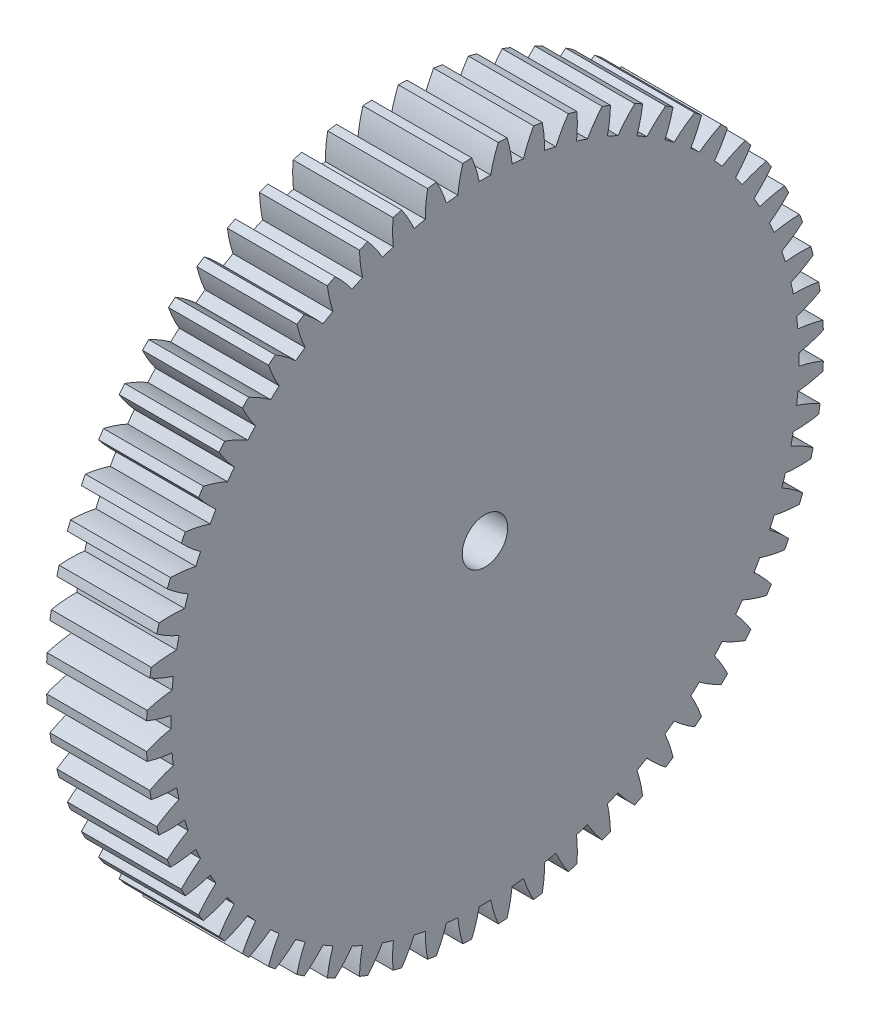
SolidWorks part; units mm, degrees
ref_plane "Plane1" through (0, 0, 0) normal (0, 0, 1) x (1, 0, 0)
ref_plane "Plane2" through (0, 0, 0) normal (0, 1, 0) x (1, 0, 0)
ref_plane "Plane3" through (0, 0, 0) normal (1, 0, 0) x (0, 0, -1)
other "Configuration Table"
sketch "HoldingSke" plane through (0, 0, 0) normal (0, 1, 0) x (1, 0, 0)
  line L0 (0, 0) -> (0.8333, -1.4434)
  line L1 (-15, 0) -> (100, 0) construction
  line L2 (0, 0) -> (-2.1039, 2.3779)
  line L3 (0, 0) -> (-11.863, 4.5341)
  line L4 (0, 0) -> (4.318, 7.479)
  line L5 (0, 0) -> (-46.8476, -17.4728)
  line L6 (0, 0) -> (-4.551, -3.0706)
  line L7 (-2.1039, 2.3779) -> (8.6586, 51.2059)
  line L8 (-76.2, 54.61) -> (-76.1, 54.61)
  line L9 (-67.7845, 28.3722) -> (-49.3413, 33.142)
  line L10 (-76.2, 71.12) -> (104.1128, 71.12)
  line L11 (0, 0) -> (-5.49, 0)
  line L12 (-76.2, 101.6) -> (-76.177, 101.6)
  line L13 (24.9733, 27.94) -> (52.9518, 28.4284)
  line L14 (24.9733, 27.94) -> (24.9743, 27.94)
  line L15 (24.9733, 27.94) -> (100.4006, 29.5858)
  line L16 (-63.627, -0.6) -> (-12.827, -0.6)
  circle A0 centre (0, 0) radius 0.4
  circle A1 centre (0, 0) radius 17.249
  circle A2 centre (0, 0) radius 37.5
  circle A3 centre (0, 0) radius 0.4
  dimension "MHD" = 34.498
  dimension "Hub_dia" = 75
  dimension "Bore" = 0.8
  dimension "MBD" = 0.8
  dimension "Num_teeth" = 60
  dimension "Pitch" = 1.6667
  dimension "Overall_len" = 50
  dimension "Show_teeth" = 60
  dimension "Thickness" = 5.49
  dimension "OAL" = 50.0001
  dimension "T_dim" = 0.1
  dimension "Ap" = 14.5
  dimension "H" = 19.05
  dimension "Pitch_radius" = 180.3128
  dimension "Width" = 5.49
  dimension "Backlash" = 0.023
  dimension "Addendum_fac" = 1
  dimension "Dedendum_fac" = 1.25
  dimension "Clearance_fac" = 0.25
  dimension "Dedendum_add" = 0.001
  dimension "Module" = 0.6
sketch "BasProSke" plane through (0, 0, 0) normal (0, 1, 0) x (1, 0, 0)
  line L0 (-10, 0) -> (60, 0) construction
  line L1 (0, 0) -> (0, 18.6)
  line L2 (0, 0) -> (5.49, 0)
  line L3 (5.49, 0) -> (5.49, 18.6)
  line L4 (5.49, 18.6) -> (0, 18.6)
  dimension "Thickness" = 5.49
  dimension "Diameter" = 37.2
revolve "Base-Revolve" add sketch "BasProSke" angle 360 about L0
sketch "TooCutSke" plane through (0, 0, 0) normal (1, 0, 0) x (0, 0, -1)
  line L1 (0, 0) -> (0, 107) construction
  line L2 (0, 0) -> (-0.5114, 17.9927) construction
  line L3 (0, 0) -> (-1.8836, 35.9404) construction
  line L4 (-0.5114, 17.9927) -> (-0.9418, 17.9702) construction
  arc A0 (0.3153, 17.2461) -> (-0.3153, 17.2461) centre (0, 0) ccw
  arc A1 (0.7414, 18.6106) -> (-0.7414, 18.6106) centre (0, 0) ccw
  circle A2 centre (0, 0) radius 18 construction
  circle A3 centre (0, 0) radius 17.4267 construction
  arc A4 (-0.3153, 17.2461) -> (-0.7414, 18.6106) centre (-7.3671, 15.7928) ccw
  arc A5 (0.7414, 18.6106) -> (0.3153, 17.2461) centre (7.3671, 15.7928) ccw
  dimension "Root_dia" = 34.498
  dimension "Overcut_dia" = 37.2508
  dimension "Pitch_dia" = 36
  dimension "Base_dia" = 34.8533
  dimension "Flank_rad" = 7.2
  dimension "Half_ang" = 3
  dimension "Half_CT" = 0.4309
extrude "ToothCut" cut sketch "TooCutSke" along normal through all
fillet "Breaks" [suppressed] radius 0.012
fillet "RootFillets" [suppressed] radius 0.151
pattern_circular "TeethCuts" count 60 every 6 about axis through (-10, 0, 0) along (1, 0, 0) of "ToothCut", "RootFillets", "Breaks"
sketch "HubNeaOneSke" plane through (0, 0, 0) normal (-1, 0, 0) x (0, 0, 1)
  circle A0 centre (0, 0) radius 17.249
  dimension "Diameter" = 34.498
extrude "HubNearOne" [suppressed] add sketch "HubNeaOneSke" along normal blind 44.5101
sketch "HubNeaBotSke" plane through (0, 0, 0) normal (-1, 0, 0) x (0, 0, 1)
  circle A0 centre (0, 0) radius 17.249
  dimension "Diameter" = 34.498
extrude "HubNearBoth" [suppressed] add sketch "HubNeaBotSke" along normal blind 22.255
ref_plane "FarPln" through (5.49, 0, 0) normal (1, 0, 0) x (0, 0, -1)
sketch "HubFarSke" plane through (5.49, 0, 0) normal (1, 0, 0) x (0, 0, -1)
  circle A0 centre (0, 0) radius 17.249
  dimension "Diameter" = 34.498
extrude "HubFar" [suppressed] add sketch "HubFarSke" along normal blind 22.255
sketch "BorSke" plane through (0, 0, 0) normal (1, 0, 0) x (0, 0, -1)
  circle A0 centre (0, 0) radius 0.4
  dimension "Diameter" = 0.8
extrude "Bore" cut sketch "BorSke" along normal mid plane 100.0001
sketch "KeySke" plane through (0, 0, 0) normal (1, 0, 0) x (0, 0, -1)
  line L0 (-0.05, 0) -> (-0.05, 0.5)
  line L1 (-0.05, 0.5) -> (0.05, 0.5)
  line L2 (0.05, 0.5) -> (0.05, 0)
  line L3 (0, 0) -> (0, 34) construction
  line L4 (-0.05, 0) -> (0.05, 0)
  dimension "Offset" = 0.5
  dimension "Width" = 0.1
extrude "Keyway" [suppressed] cut sketch "KeySke" along normal mid plane 100.0001
pattern_circular "Keyway2" [suppressed] count 2 every 90 about axis through (-10, 0, 0) along (1, 0, 0)
sketch "Sketch1" plane through (5.49, 0, 0) normal (1, 0, 0) x (0, 0, -1)
  circle A0 centre (0, 0) radius 1.25
  dimension "D1" = 2.5
extrude "Cut-Extrude1" cut sketch "Sketch1" against normal through all
equation "' \"Module@HoldingSke\" = 6.35"
equation "' \"Num_teeth@HoldingSke\" = 12"
equation "' \"Ap@HoldingSke\" =  20"
equation "' \"Ap@HoldingSke\" = 20"
equation "' \"Width@HoldingSke\" = 0.5 * 25.4"
equation "' \"Hub_dia@HoldingSke\"= 1 * 25.4"
equation "' \"Hub_dia@HoldingSke\" = 1 * 25.4"
equation "' \"Overall_len@HoldingSke\" = 1.0 * 25.4"
equation "' \"Bore@HoldingSke\" = 0.75 * 25.4"
equation "' \"T_dim@HoldingSke\" = 0.1 * 25.4"
equation "' \"Width@KeySke\" = 0.25 * 25.4"
equation "' \"Show_teeth@HoldingSke\" = 13"
equation "' \"Backlash@HoldingSke\" = 0.009 * 25.4"
equation "' \"Addendum_fac@HoldingSke\" = 1.0"
equation "' \"Dedendum_fac@HoldingSke\" = 1.25"
equation "' \"Dedendum_add@HoldingSke\" = 0.00005 * 25.4"
equation "' \"Clearance_fac@HoldingSke\" = 0.25"
equation "\"Pitch@HoldingSke\" = 1 / \"Module@HoldingSke\""
equation "\"Overcut_dia@TooCutSke\" = (\"Num_teeth@HoldingSke\" + 2 * \"Addendum_fac@HoldingSke\") / \"Pitch@HoldingSke\" + 0.002 * 25.4"
equation "\"Pitch_dia@TooCutSke\" = \"Num_teeth@HoldingSke\" / \"Pitch@HoldingSke\""
equation "\"Base_dia@TooCutSke\" = \"Num_teeth@HoldingSke\" / \"Pitch@HoldingSke\" * cos((\"Ap@HoldingSke\"  * 3.14159265 / 180))"
equation "\"Root_dia@TooCutSke\" = (\"Num_teeth@HoldingSke\" + 2) / \"Pitch@HoldingSke\" - 2 * (\"Addendum_fac@HoldingSke\" + \"Dedendum_fac@HoldingSke\") / \"Pitch@HoldingSke\" - \"Dedendum_add@HoldingSke\" * 2"
equation "\"Half_ang@TooCutSke\" = 180 / \"Num_teeth@HoldingSke\""
equation "\"Half_CT@TooCutSke\" = \"Num_teeth@HoldingSke\" / \"Pitch@HoldingSke\" * sin((3.14159265 / 2 / \"Num_teeth@HoldingSke\")) / 2 - 7 * \"Backlash@HoldingSke\" / 4"
equation "\"Flank_rad@TooCutSke\" = \"Num_teeth@HoldingSke\" / \"Pitch@HoldingSke\" / 5"
equation "\"Radius@RootFillets\" = \"Clearance_fac@HoldingSke\" / \"Pitch@HoldingSke\" + \"Dedendum_add@HoldingSke\""
equation "\"Break_rad@Breaks\" = 0.02 / \"Pitch@HoldingSke\""
equation "\"Thickness@HoldingSke\" = \"Width@HoldingSke\""
equation "\"OAL@HoldingSke\" = \"Thickness@HoldingSke\""
equation "\"MHD@HoldingSke\" = (\"Num_teeth@HoldingSke\" + 2) / \"Pitch@HoldingSke\" - 2 * (\"Addendum_fac@HoldingSke\" + \"Dedendum_fac@HoldingSke\")  / \"Pitch@HoldingSke\" - \"Dedendum_add@HoldingSke\" * 2"
equation "\"MBD@HoldingSke\" = (\"Num_teeth@HoldingSke\" + 2) / \"Pitch@HoldingSke\" - 2 * (\"Addendum_fac@HoldingSke\" + \"Dedendum_fac@HoldingSke\")  / \"Pitch@HoldingSke\" - \"Dedendum_add@HoldingSke\" * 2 - 0.002 * 25.4"
equation "\"MHD@HoldingSke\" = ((sgn( \"MHD@HoldingSke\" - \"Hub_dia@HoldingSke\" )-1)*( \"MHD@HoldingSke\" - \"Hub_dia@HoldingSke\" ))/-2+ \"Hub_dia@HoldingSke\""
equation "\"MBD@HoldingSke\" = ((sgn( \"MBD@HoldingSke\" - \"Bore@HoldingSke\" )-1)*( \"MBD@HoldingSke\" - \"Bore@HoldingSke\" ))/-2+ \"Bore@HoldingSke\""
equation "\"OAL@HoldingSke\" = ((sgn( \"OAL@HoldingSke\" - \"Overall_len@HoldingSke\" )+1)*( \"OAL@HoldingSke\" - \"Overall_len@HoldingSke\" ))/2 + \"Overall_len@HoldingSke\" + 0.000002 * 25.4"
equation "\"Num_teeth@TeethCuts\" = int( \"Show_teeth@HoldingSke\" ) + 1"
equation "\"Num_teeth@TeethCuts\" = ((sgn( \"Num_teeth@TeethCuts\" - \"Num_teeth@HoldingSke\" )-1)*( \"Num_teeth@TeethCuts\" - \"Num_teeth@HoldingSke\" ))/-2+ \"Num_teeth@HoldingSke\""
equation "\"Num_teeth@TeethCuts\" = ((sgn( \"Num_teeth@TeethCuts\" - 2.0)+1)*( \"Num_teeth@TeethCuts\" - 2.0))/2 +2.0"
equation "\"Angle@TeethCuts\" = 360.0 / \"Num_teeth@HoldingSke\""
equation "\"Diameter@BasProSke\" = (\"Num_teeth@HoldingSke\" + 2 * \"Addendum_fac@HoldingSke\") / \"Pitch@HoldingSke\""
equation "\"Thickness@BasProSke\"  = \"Thickness@HoldingSke\""
equation "' \"Fillet_rad@BasProSke\" =  \"Thickness@HoldingSke\" * 0.05"
equation "' \"Fillet_rad@BasProSke\" = \"Thickness@HoldingSke\" * 0.05"
equation "\"MHD@HoldingSke\" = ((sgn( \"MHD@HoldingSke\" - \"Root_dia@TooCutSke\" )-1)*( \"MHD@HoldingSke\" - \"Root_dia@TooCutSke\" ))/-2+ \"Root_dia@TooCutSke\""
equation "\"Diameter@HubNeaOneSke\" = \"MHD@HoldingSke\""
equation "\"Length@HubNearOne\" = \"OAL@HoldingSke\" - \"Thickness@BasProSke\""
equation "\"Diameter@HubNeaBotSke\" = \"MHD@HoldingSke\""
equation "\"Length@HubNearBoth\" = ( \"OAL@HoldingSke\" - \"Thickness@BasProSke\" ) / 2.0"
equation "\"Thickness@FarPln\" = \"Thickness@BasProSke\""
equation "\"Diameter@HubFarSke\" = \"MHD@HoldingSke\""
equation "\"Length@HubFar\" = ( \"OAL@HoldingSke\" - \"Thickness@BasProSke\" ) / 2.0"
equation "\"Diameter@BorSke\" = \"MBD@HoldingSke\""
equation "\"D1@Bore\" = \"OAL@HoldingSke\" * 2.0"
equation "\"D1@Keyway\" = \"OAL@HoldingSke\" * 2.0"
equation "\"Offset@KeySke\" = \"T_dim@HoldingSke\" + \"MBD@HoldingSke\" / 2.0"
